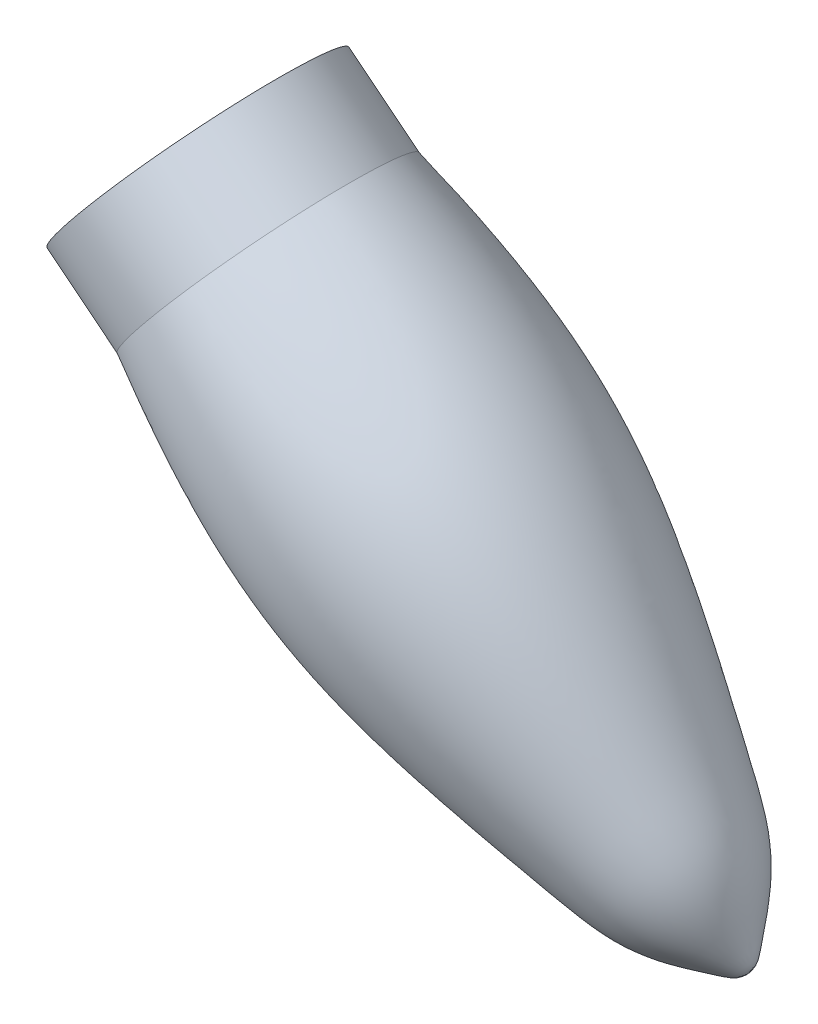
SolidWorks part; units mm, degrees
ref_plane "前基準面" through (0, 0, 0) normal (0, 0, 1) x (1, 0, 0)
ref_plane "上基準面" through (0, 0, 0) normal (0, 1, 0) x (1, 0, 0)
ref_plane "右基準面" through (0, 0, 0) normal (1, 0, 0) x (0, 0, -1)
sketch "草圖1" plane through (0, 0, 0) normal (0, 0, 1) x (1, 0, 0)
  line L0 (24.0586, 13.3133) -> (25.4223, 3.0957)
  line L1 (25.4223, 3.0957) -> (46.2478, -13.597)
  spline S0 degree 3 poles (24.0586, 13.3133) (34.2703, 7.6934) (37.4191, 3.6846) (46.0678, -8.9055) (46.2308, -11.0861) (46.513, -13.0864) (46.3692, -13.4455) (46.2478, -13.597) knots 0 0 0 0 0.462354 0.501037 0.589057 0.601322 0.612689 0.612689 0.612689 0.612689
revolve "旋轉1" add sketch "草圖1" angle 360 about L1
ref_plane "平面1" through (8.1506, -6.5332, 0) normal (-0.7803, 0.6254, 0) x (0, 0, 1)
sketch "草圖2" plane through (8.1506, -6.5332, 0) normal (-0.7803, 0.6254, 0) x (0, 0, 1)
  circle A0 centre (0, 18.3154) radius 7.1197
extrude "填料-伸長1" add sketch "草圖2" along normal blind 5 separate body
